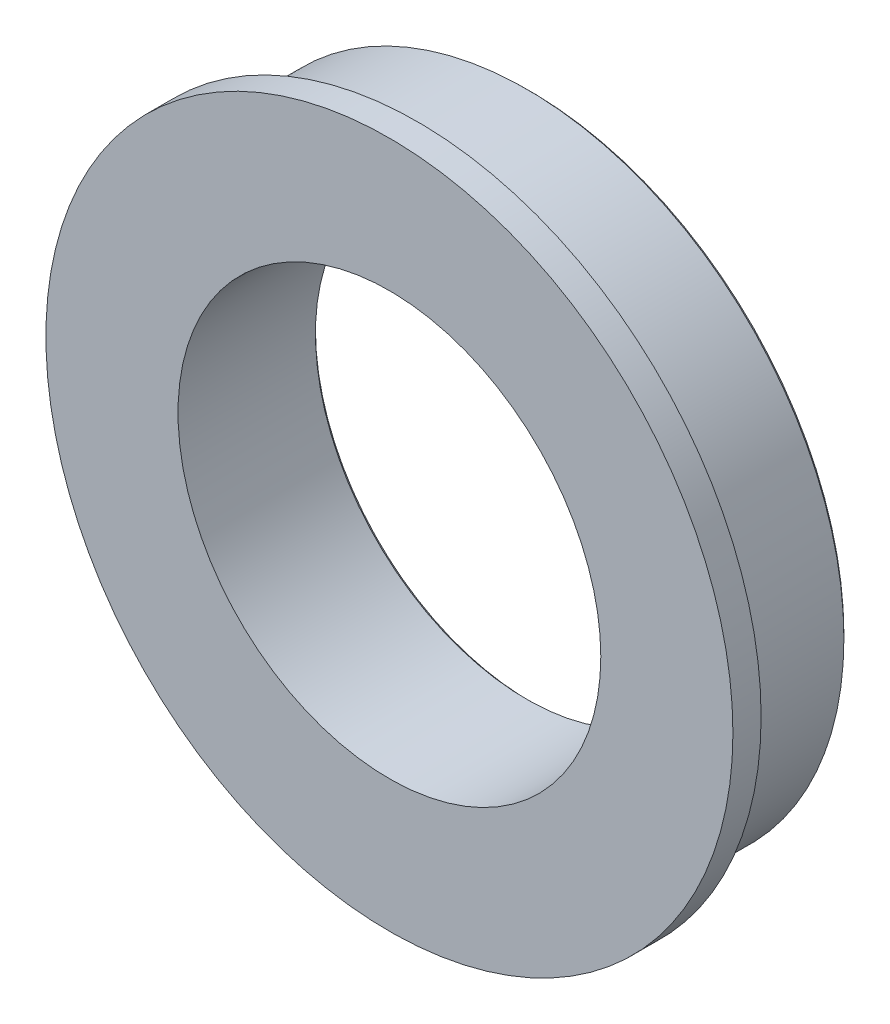
SolidWorks part; units mm, degrees
material "1023 碳钢板 (SS)"
ref_plane "前视基准面" through (0, 0, 0) normal (0, 0, 1) x (1, 0, 0)
ref_plane "上视基准面" through (0, 0, 0) normal (0, 1, 0) x (1, 0, 0)
ref_plane "右视基准面" through (0, 0, 0) normal (1, 0, 0) x (0, 0, -1)
other "Configuration Table"
sketch "草图1" plane through (0, 0, 0) normal (0, 0, 1) x (1, 0, 0)
  circle A0 centre (0, 0) radius 6
  circle A1 centre (0, 0) radius 9
  dimension "D1" = 12
  dimension "D2" = 18
extrude "凸台-拉伸1" add sketch "草图1" along normal blind 4
chamfer "倒角1" distance 0.1 angle 45 2 edges at (6, 0, 0) (9, 0, 0)
sketch "草图2" plane through (0, 0, 4) normal (0, 0, 1) x (1, 0, 0)
  circle A0 centre (0, 0) radius 6
  circle A1 centre (0, 0) radius 9.75
  dimension "D1" = 19.5
extrude "凸台-拉伸2" add sketch "草图2" against normal blind 0.8
